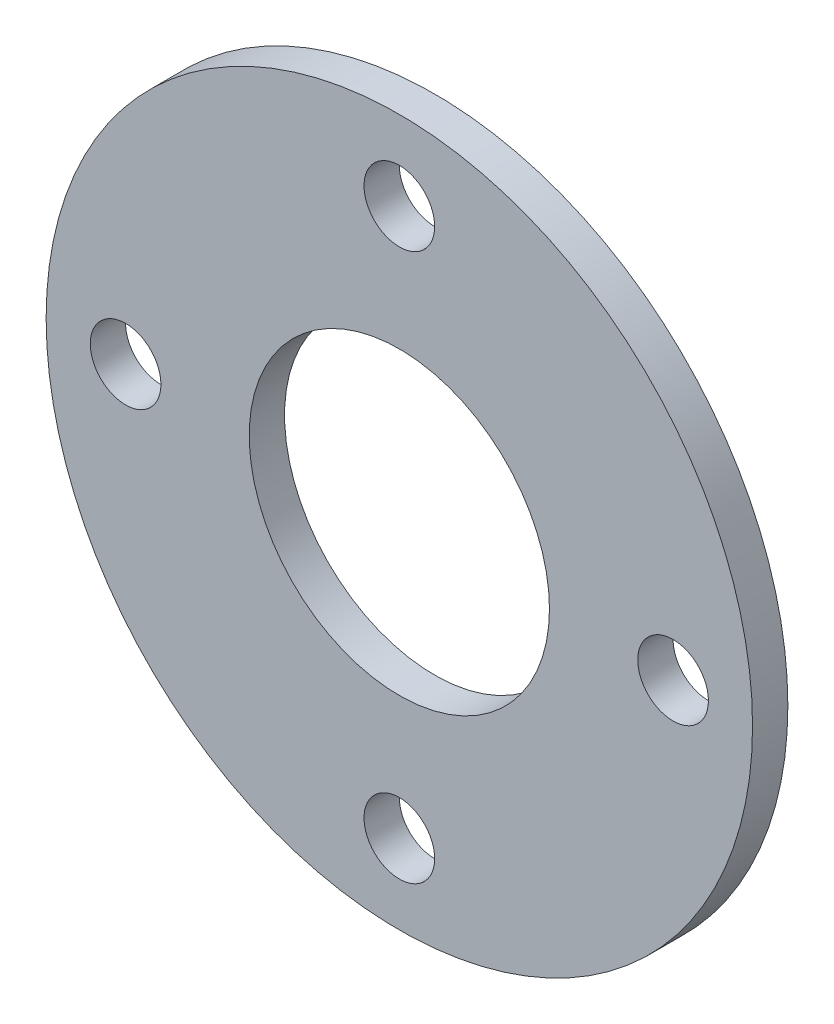
SolidWorks part; units mm, degrees
ref_plane "前视基准面" through (0, 0, 0) normal (0, 0, 1) x (1, 0, 0)
ref_plane "上视基准面" through (0, 0, 0) normal (0, 1, 0) x (1, 0, 0)
ref_plane "右视基准面" through (0, 0, 0) normal (1, 0, 0) x (0, 0, -1)
sketch "草图2" plane through (0, 0, 0) normal (0, 0, 1) x (1, 0, 0)
  line L0 (0, 0) -> (46.0269, 0) construction
  line L1 (0, 0) -> (0, 27.097) construction
  circle A0 centre (0, 0) radius 20
  circle A1 centre (0, 0) radius 15.5 construction
  circle A2 centre (0, 0) radius 8.5
  circle A3 centre (0, 15.5) radius 2
  circle A4 centre (0, -15.5) radius 2
  circle A5 centre (15.5, 0) radius 2
  circle A6 centre (-15.5, 0) radius 2
  dimension "D1" = 17
  dimension "D2" = 40
  dimension "D3" = 31
extrude "凸台-拉伸1" add sketch "草图2" along normal blind 2
